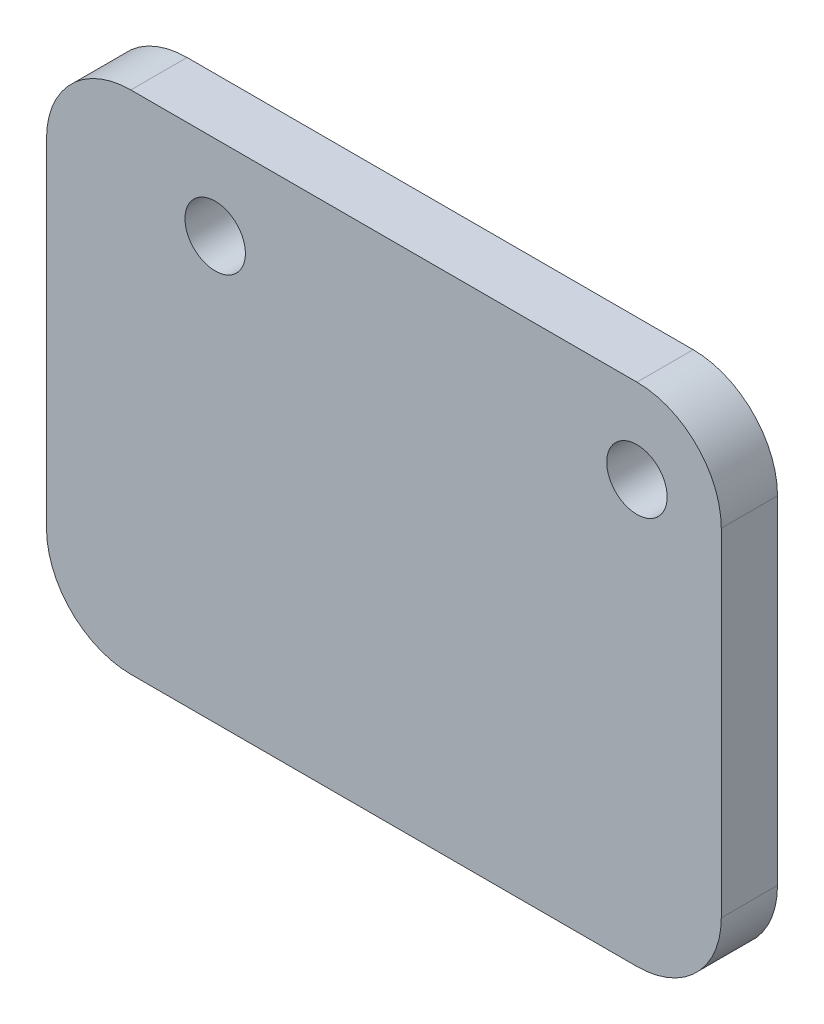
SolidWorks part; units mm, degrees
ref_plane "前视基准面" through (0, 0, 0) normal (0, 0, 1) x (1, 0, 0)
ref_plane "上视基准面" through (0, 0, 0) normal (0, 1, 0) x (1, 0, 0)
ref_plane "右视基准面" through (0, 0, 0) normal (1, 0, 0) x (0, 0, -1)
sketch "草图1" plane through (0, 0, 0) normal (0, 0, 1) x (1, 0, 0)
  line L0 (0, 0) -> (24, 0)
  line L1 (24, 0) -> (24, -18)
  line L2 (24, -18) -> (0, -18)
  line L3 (0, -18) -> (0, 0)
  circle A0 centre (21, -3) radius 1.075
  circle A1 centre (6, -3) radius 1.075
  dimension "D3" = 2.15
  dimension "D4" = 2.15
  dimension "D1" = 24
  dimension "D2" = 18
  dimension "D5" = 3
  dimension "D6" = 3
  dimension "D7" = 18
  dimension "D8" = 3
extrude "凸台-拉伸1" add sketch "草图1" along normal blind 2
fillet "圆角1" radius 3 1 edges at (24, 0, 1)
fillet "圆角2" radius 3 1 edges at (0, 0, 1)
fillet "圆角3" radius 3 1 edges at (0, -18, 1)
fillet "圆角4" radius 3 1 edges at (24, -18, 1)
